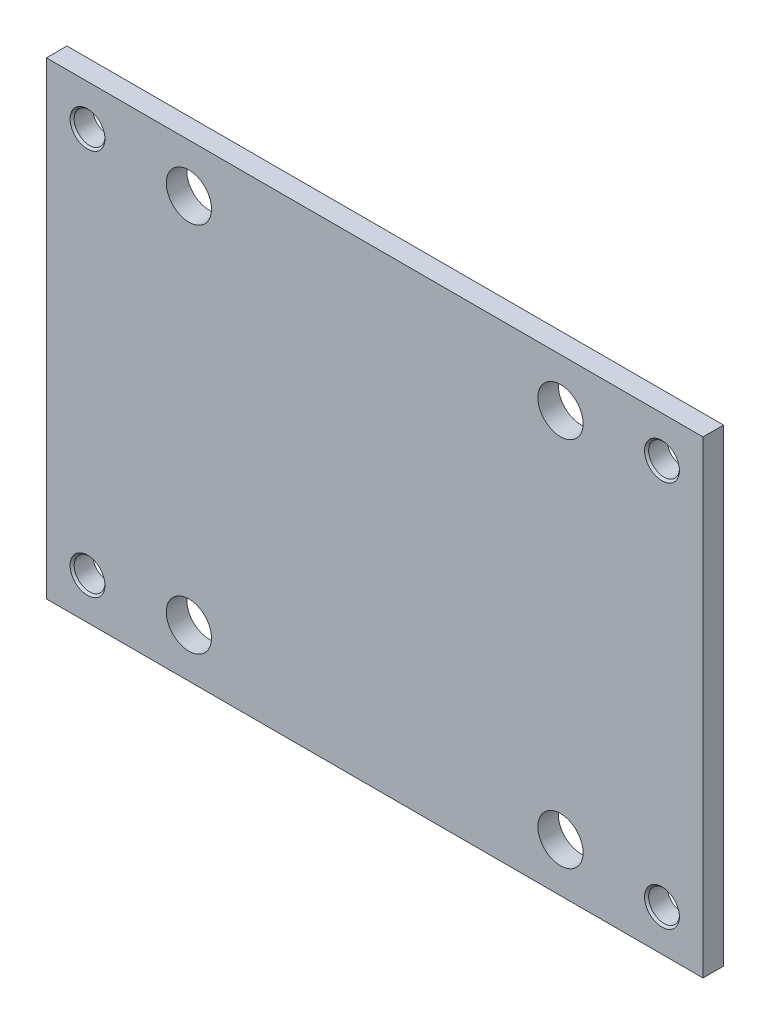
SolidWorks part; units mm, degrees
ref_plane "Front Plane" through (0, 0, 0) normal (0, 0, 1) x (1, 0, 0)
ref_plane "Top Plane" through (0, 0, 0) normal (0, 1, 0) x (1, 0, 0)
ref_plane "Right Plane" through (0, 0, 0) normal (1, 0, 0) x (0, 0, -1)
sketch "Sketch1" plane through (0, 0, 0) normal (0, 0, 1) x (1, 0, 0)
  line L1 (-101.6, 72.517) -> (101.6, 72.517)
  line L2 (-101.6, 72.517) -> (-101.6, -72.517)
  line L3 (-101.6, -72.517) -> (101.6, -72.517)
  line L4 (101.6, 72.517) -> (101.6, -72.517)
  line L5 (-101.6, 72.517) -> (101.6, -72.517) construction
  line L6 (-101.6, -72.517) -> (101.6, 72.517) construction
  point P0 (0, 0)
  dimension "D1" = 203.2
  dimension "D2" = 145.034
extrude "Boss-Extrude1" add sketch "Sketch1" along normal blind 6.35
hole_wizard "3/8 (0.375) Diameter Hole1" positions "Sketch2" profile "Sketch3" hole size "3/8" standard "ANSI Inch" end condition through all
sketch "Sketch2" plane through (0, 0, 6.35) normal (0, 0, 1) x (1, 0, 0)
  line L0 (-101.6, 72.517) -> (-101.6, -72.517) construction
  line L1 (101.6, 72.517) -> (-101.6, 72.517) construction
  line L3 (101.6, -72.517) -> (101.6, 72.517) construction
  line L4 (-101.6, -72.517) -> (101.6, -72.517) construction
  point P0 (-88.9, 59.817)
  point P2 (-88.9, -59.817)
  point P4 (88.9, -59.817)
  point P6 (88.9, 59.817)
  dimension "D1" = 12.7
  dimension "D2" = 12.7
  dimension "D3" = 12.7
  dimension "D4" = 12.7
  dimension "D5" = 12.7
  dimension "D6" = 12.7
  dimension "D7" = 12.7
  dimension "D8" = 12.7
sketch "Sketch3" plane through (-88.9, 59.817, 6.35) normal (1, 0, 0) x (0, -1, 0)
  line L0 (0, 0) -> (0, 6.35)
  line L1 (0, 6.35) -> (4.7625, 6.35)
  line L2 (4.7625, 6.35) -> (4.7625, 0.635)
  line L3 (4.7625, 0.635) -> (5.3975, 0)
  line L5 (5.3975, 0) -> (0, 0)
  line L6 (-4.7625, 0.635) -> (-5.3975, 0) construction
  line L11 (0, -6.35) -> (0, 107.95) construction
  dimension "Thru Hole Dia." = 9.525
  dimension "Thru Hole Depth" = 6.35
  dimension "Near C'Sink Dia." = 10.795
  dimension "Near C'Sink Angle" = 90
sketch3d "3DSketch1"
  line L0 (101.6, -72.517, 0) -> (101.6, 72.517, 0) construction
  line L1 (101.6, -72.517, 6.35) -> (101.6, 72.517, 6.35) construction
  line L2 (-101.6, 72.517, 0) -> (-101.6, -72.517, 0) construction
  line L3 (101.6, 72.517, 0) -> (-101.6, 72.517, 0) construction
  line L4 (-101.6, -72.517, 0) -> (101.6, -72.517, 0) construction
  line L5 (101.6, 72.517, 6.35) -> (-101.6, 72.517, 6.35) construction
  point P0 (101.6, 0, 0)
  point P1 (101.6, 0, 6.35)
  point P4 (-101.6, 0, 0)
  point P7 (0, 72.517, 0)
  point P10 (0, -72.517, 0)
  point P13 (0, 72.517, 6.35)
ref_plane "Plane1" through (0, 0, 0) normal (0, -1, 0) x (-1, 0, 0)
ref_plane "Plane2" through (0, 0, 0) normal (-1, 0, 0) x (0, 0, 1)
sketch "Sketch4" plane through (0, 0, 0) normal (0, 0, -1) x (-1, 0, 0)
  line L4 (-101.6, 72.517) -> (101.6, 72.517) construction
  circle A0 centre (-57.483, 57.517) radius 7
  circle A1 centre (57.517, 57.517) radius 7
  circle A2 centre (57.517, -57.483) radius 7
  circle A3 centre (-57.483, -57.483) radius 7
  point P12 (0, 72.517)
  point P13 (72.517, 72.517)
  dimension "D1" = 72.517
extrude "Cut-Extrude1" cut sketch "Sketch4" against normal through all
sketch "Sketch5" plane through (0, 0, 0) normal (0, 0, -1) x (-1, 0, 0)
  line L4 (-101.6, 72.517) -> (-101.6, -72.517)
  line L5 (-101.6, -72.517) -> (101.6, -72.517)
  line L6 (101.6, -72.517) -> (101.6, 72.517)
  line L7 (101.6, 72.517) -> (-101.6, 72.517)
  line L8 (-101.6, 72.517) -> (-101.6, -72.517)
  line L9 (-101.6, -72.517) -> (101.6, -72.517)
  line L10 (101.6, -72.517) -> (101.6, 72.517)
  line L11 (101.6, 72.517) -> (-101.6, 72.517)
  circle A0 centre (-88.9, 59.817) radius 4.7625 construction
  circle A2 centre (57.517, 57.517) radius 7 construction
  circle A3 centre (88.9, 59.817) radius 4.7625 construction
  circle A4 centre (-57.483, -57.483) radius 7 construction
  circle A5 centre (-88.9, -59.817) radius 4.7625 construction
  circle A6 centre (57.517, -57.483) radius 7 construction
  circle A7 centre (88.9, -59.817) radius 4.7625 construction
  circle A8 centre (88.9, -59.817) radius 4.7625
  circle A9 centre (57.517, -57.483) radius 7
  circle A10 centre (-88.9, -59.817) radius 4.7625
  circle A11 centre (-57.483, -57.483) radius 7
  circle A12 centre (-88.9, 59.817) radius 4.7625
  circle A13 centre (57.517, 57.517) radius 7
  circle A14 centre (88.9, 59.817) radius 4.7625
  circle A15 centre (-57.483, 57.517) radius 7 construction
  circle A16 centre (-57.483, 57.517) radius 7
  point P28 (0, 72.517)
  dimension "D1" = 0
